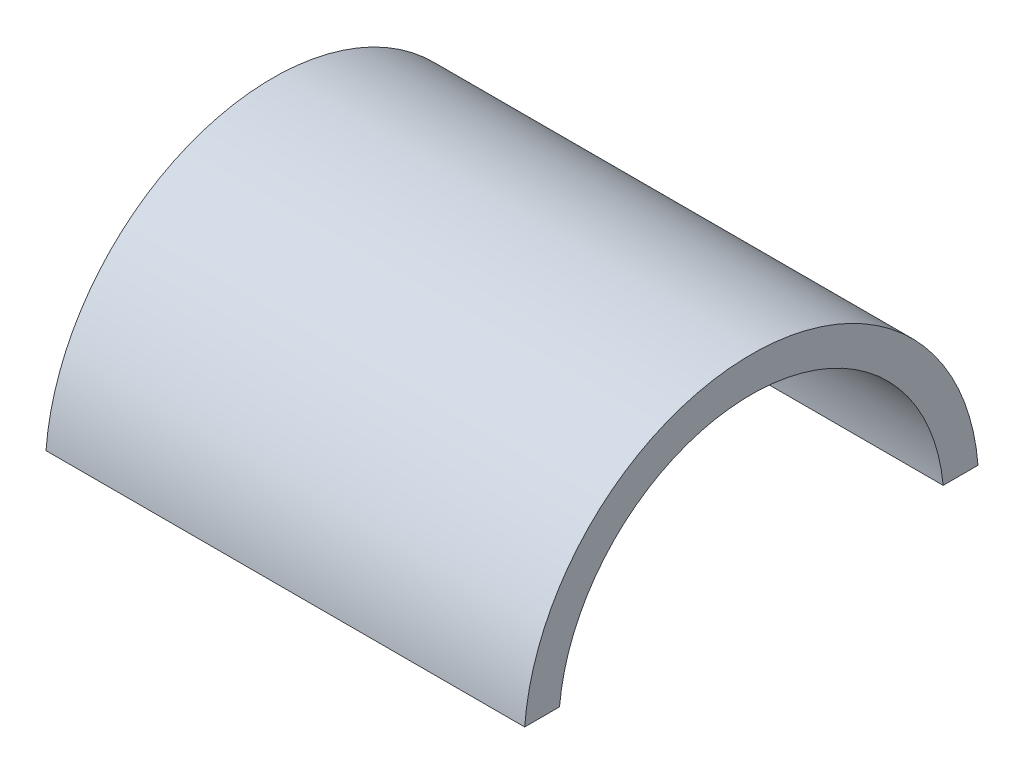
SolidWorks part; units mm, degrees
material "ABS"
ref_plane "Front Plane" through (0, 0, 0) normal (0, 0, 1) x (1, 0, 0)
ref_plane "Top Plane" through (0, 0, 0) normal (0, 1, 0) x (1, 0, 0)
ref_plane "Right Plane" through (0, 0, 0) normal (1, 0, 0) x (0, 0, -1)
sketch "Sketch1" plane through (0, 0, 0) normal (1, 0, 0) x (0, 0, -1)
  line L0 (-24.0547, 1.905) -> (-20.3581, 1.905)
  line L1 (20.3581, 1.905) -> (24.0547, 1.905)
  arc A0 (24.0547, 1.905) -> (-24.0547, 1.905) centre (0, 0) ccw
  arc A1 (20.3581, 1.905) -> (-20.3581, 1.905) centre (0, 0) ccw
  point P1 (0, 24.13)
  dimension "D1" = 40.894
  dimension "D2" = 48.26
  dimension "D3" = 22.225
extrude "Boss-Extrude1" add sketch "Sketch1" along normal mid plane 50.8
